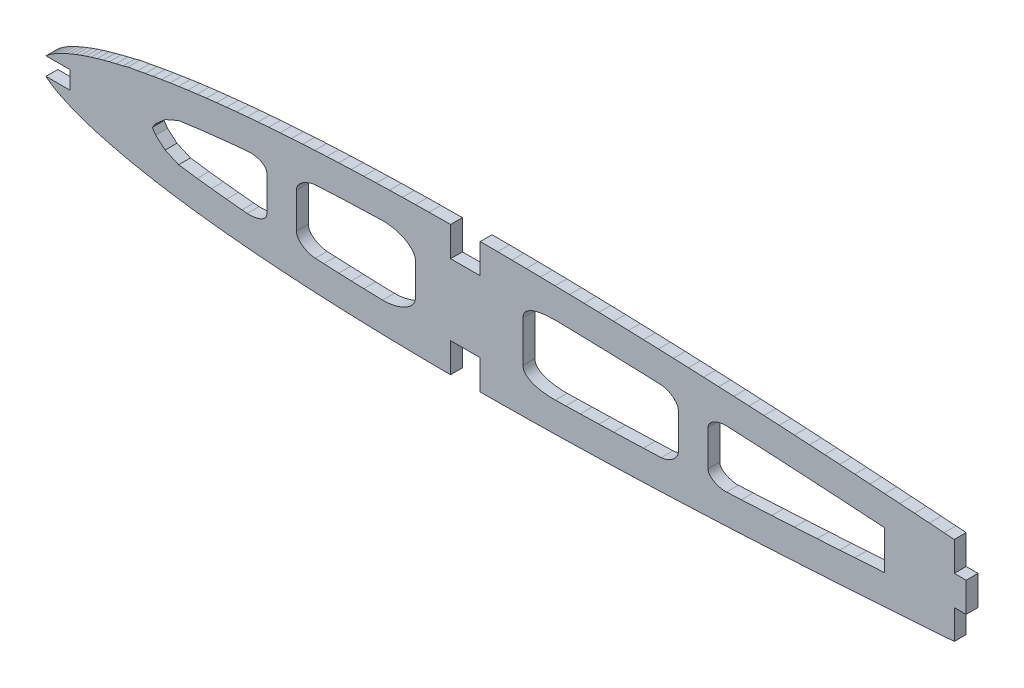
SolidWorks part; units mm, degrees
ref_plane "前视基准面" through (0, 0, 0) normal (0, 0, 1) x (1, 0, 0)
ref_plane "上视基准面" through (0, 0, 0) normal (0, 1, 0) x (1, 0, 0)
ref_plane "右视基准面" through (0, 0, 0) normal (1, 0, 0) x (0, 0, -1)
sketch "Model" plane through (0, 0, 0) normal (0, 0, 1) x (1, 0, 0)
  line L0 (365.1559, -97.3973) -> (369.2164, -97.3973)
  line L1 (369.2164, -97.3973) -> (369.2164, -100.3973)
  line L2 (369.2164, -100.3973) -> (365.1559, -100.3973)
  line L3 (438.4064, -87.9083) -> (438.4104, -92.9083)
  line L4 (438.4104, -92.9083) -> (433.4104, -92.9143)
  line L5 (433.4104, -92.9143) -> (433.4064, -87.9143)
  line L6 (438.4064, -109.8863) -> (438.4124, -104.8863)
  line L7 (438.4124, -104.8863) -> (433.4124, -104.8803)
  line L8 (433.4124, -104.8803) -> (433.4064, -109.8803)
  line L9 (518.3903, -91.444) -> (516.6664, -91.3183)
  line L10 (516.6664, -91.3183) -> (514.1714, -91.1393)
  line L11 (514.1714, -91.1393) -> (511.6764, -90.9633)
  line L12 (511.6764, -90.9633) -> (509.1804, -90.7903)
  line L13 (509.1804, -90.7903) -> (506.6554, -90.6183)
  line L14 (506.6554, -90.6183) -> (504.1314, -90.4503)
  line L15 (504.1314, -90.4503) -> (501.6054, -90.2873)
  line L16 (501.6054, -90.2873) -> (499.0594, -90.1283)
  line L17 (499.0594, -90.1283) -> (496.5144, -89.9743)
  line L18 (496.5144, -89.9743) -> (493.9684, -89.8233)
  line L19 (493.9684, -89.8233) -> (491.4134, -89.6743)
  line L20 (491.4134, -89.6743) -> (488.8584, -89.5283)
  line L21 (488.8584, -89.5283) -> (486.3034, -89.3863)
  line L22 (486.3034, -89.3863) -> (483.7484, -89.2513)
  line L23 (483.7484, -89.2513) -> (481.1944, -89.1213)
  line L24 (481.1944, -89.1213) -> (478.6384, -88.9983)
  line L25 (478.6384, -88.9983) -> (476.0924, -88.8813)
  line L26 (476.0924, -88.8813) -> (473.5474, -88.7693)
  line L27 (473.5474, -88.7693) -> (471.0014, -88.6633)
  line L28 (471.0014, -88.6633) -> (468.4764, -88.5643)
  line L29 (468.4764, -88.5643) -> (465.9524, -88.4703)
  line L30 (465.9524, -88.4703) -> (463.4264, -88.3833)
  line L31 (463.4264, -88.3833) -> (460.9314, -88.3033)
  line L32 (460.9314, -88.3033) -> (458.4364, -88.2303)
  line L33 (458.4364, -88.2303) -> (455.9404, -88.1633)
  line L34 (455.9404, -88.1633) -> (453.4854, -88.1043)
  line L35 (453.4854, -88.1043) -> (451.0314, -88.0523)
  line L36 (451.0314, -88.0523) -> (448.5764, -88.0073)
  line L37 (448.5764, -88.0073) -> (446.1704, -87.9703)
  line L38 (446.1704, -87.9703) -> (443.7664, -87.9423)
  line L39 (443.7664, -87.9423) -> (441.3604, -87.9213)
  line L40 (441.3604, -87.9213) -> (438.4064, -87.9083)
  line L42 (387.5324, -95.6683) -> (390.6644, -95.2413)
  line L43 (390.6644, -95.2413) -> (393.0784, -94.9513)
  line L44 (393.0784, -94.9513) -> (395.6144, -94.6733)
  line L45 (395.6144, -94.6733) -> (398.2099, -94.4193)
  line L46 (398.2099, -94.4193) -> (399.256, -94.3267)
  line L47 (410.7501, -93.5242) -> (412.0079, -93.4582)
  line L48 (412.0079, -93.4582) -> (414.9885, -93.3234)
  line L49 (414.9885, -93.3234) -> (416.6574, -93.2563)
  line L50 (416.6574, -93.2563) -> (418.7714, -93.1823)
  line L51 (418.7714, -93.1823) -> (421.9864, -93.0883)
  line L52 (421.9343, -104.7047) -> (418.7714, -104.6123)
  line L53 (418.7714, -104.6123) -> (416.6574, -104.5383)
  line L54 (416.6574, -104.5383) -> (414.5434, -104.4533)
  line L55 (414.5434, -104.4533) -> (412.0079, -104.3363)
  line L56 (412.0079, -104.3363) -> (410.5909, -104.2619)
  line L57 (399.1076, -103.4547) -> (398.2099, -103.3753)
  line L58 (398.2099, -103.3753) -> (395.6144, -103.1213)
  line L59 (395.6144, -103.1213) -> (393.0784, -102.8433)
  line L60 (393.0784, -102.8433) -> (390.6644, -102.5533)
  line L61 (390.6644, -102.5533) -> (387.5324, -102.1263)
  line L62 (451.3201, -93.0601) -> (452.8362, -93.0905)
  line L63 (452.8362, -93.0905) -> (455.2997, -93.1479)
  line L64 (455.2997, -93.1479) -> (458.4364, -93.2303)
  line L65 (458.4364, -93.2303) -> (460.9314, -93.3033)
  line L66 (460.9314, -93.3033) -> (465.9524, -93.4703)
  line L67 (465.9524, -93.4703) -> (468.8582, -93.5804)
  line L68 (479.9184, -94.063) -> (482.4714, -94.1863)
  line L69 (482.4714, -94.1863) -> (487.5809, -94.4573)
  line L70 (487.5809, -94.4573) -> (491.4134, -94.6743)
  line L71 (491.4134, -94.6743) -> (495.2414, -94.8988)
  line L72 (495.2414, -94.8988) -> (499.0594, -95.1283)
  line L73 (499.0594, -95.1283) -> (501.6054, -95.2873)
  line L74 (501.6054, -95.2873) -> (506.6554, -95.6183)
  line L75 (506.6554, -102.1763) -> (501.6054, -102.5073)
  line L76 (501.6054, -102.5073) -> (499.0594, -102.6663)
  line L77 (499.0594, -102.6663) -> (495.2414, -102.8958)
  line L78 (495.2414, -102.8958) -> (491.4134, -103.1203)
  line L79 (491.4134, -103.1203) -> (487.5809, -103.3373)
  line L80 (487.5809, -103.3373) -> (482.4714, -103.6083)
  line L81 (482.4714, -103.6083) -> (479.9656, -103.7292)
  line L82 (468.9559, -104.2104) -> (465.9524, -104.3243)
  line L83 (465.9524, -104.3243) -> (460.9314, -104.4913)
  line L84 (460.9314, -104.4913) -> (458.4364, -104.5643)
  line L85 (458.4364, -104.5643) -> (455.2997, -104.6467)
  line L86 (455.2997, -104.6467) -> (452.8362, -104.704)
  line L87 (452.8362, -104.704) -> (451.0861, -104.7391)
  line L88 (387.5324, -95.6683) -> (385.2532, -96.6702)
  line L89 (385.2532, -96.6702) -> (383.6712, -98.0522)
  line L90 (383.6712, -98.0522) -> (383.078, -98.8973)
  line L91 (387.5324, -102.1263) -> (385.2532, -101.1243)
  line L92 (385.2532, -101.1243) -> (383.6712, -99.7423)
  line L93 (383.6712, -99.7423) -> (383.078, -98.8973)
  line L94 (427.4864, -96.2466) -> (427.4864, -101.548)
  line L95 (445.635, -95.4141) -> (445.635, -102.3805)
  line L96 (407.4071, -95.8973) -> (407.4071, -101.8973)
  line L97 (402.4071, -101.8973) -> (402.4071, -95.8973)
  line L98 (476.8379, -95.8973) -> (476.8379, -101.8973)
  line L99 (471.8379, -101.8973) -> (471.8379, -95.8973)
  line L100 (520.3903, -98.8973) -> (520.3903, -96.3973)
  line L101 (520.3903, -98.8973) -> (520.3903, -101.3973)
  line L102 (520.3903, -96.3973) -> (518.3903, -96.3973)
  line L103 (520.3903, -101.3973) -> (518.3903, -101.3973)
  line L104 (518.3903, -96.3973) -> (518.3903, -91.444)
  line L105 (518.3903, -101.3973) -> (518.3903, -106.3499)
  line L106 (506.6554, -95.6183) -> (506.6554, -102.1763)
  line L107 (433.4064, -87.9143) -> (429.7654, -87.9423)
  line L108 (429.7654, -87.9423) -> (427.4864, -87.9723)
  line L109 (427.4864, -87.9723) -> (425.2864, -88.0113)
  line L110 (425.2864, -88.0113) -> (423.0864, -88.0593)
  line L111 (423.0864, -88.0593) -> (420.8864, -88.1173)
  line L112 (420.8864, -88.1173) -> (418.7714, -88.1823)
  line L113 (418.7714, -88.1823) -> (416.6574, -88.2563)
  line L114 (416.6574, -88.2563) -> (414.5434, -88.3413)
  line L115 (414.5434, -88.3413) -> (412.5224, -88.4323)
  line L116 (412.5224, -88.4323) -> (410.5024, -88.5343)
  line L117 (410.5024, -88.5343) -> (408.4824, -88.6463)
  line L118 (408.4824, -88.6463) -> (406.5644, -88.7643)
  line L119 (406.5644, -88.7643) -> (404.6474, -88.8943)
  line L120 (404.6474, -88.8943) -> (402.7304, -89.0353)
  line L121 (402.7304, -89.0353) -> (400.9214, -89.1793)
  line L122 (400.9214, -89.1793) -> (399.1134, -89.3353)
  line L123 (399.1134, -89.3353) -> (397.3064, -89.5033)
  line L124 (397.3064, -89.5033) -> (395.6144, -89.6733)
  line L125 (395.6144, -89.6733) -> (393.9234, -89.8543)
  line L126 (393.9234, -89.8543) -> (392.2334, -90.0483)
  line L127 (392.2334, -90.0483) -> (390.6644, -90.2413)
  line L128 (390.6644, -90.2413) -> (389.0974, -90.4483)
  line L129 (389.0974, -90.4483) -> (387.5324, -90.6683)
  line L130 (387.5324, -90.6683) -> (386.0934, -90.8853)
  line L131 (386.0934, -90.8853) -> (384.6574, -91.1153)
  line L132 (384.6574, -91.1153) -> (383.2234, -91.3593)
  line L133 (383.2234, -91.3593) -> (381.9184, -91.5963)
  line L134 (381.9184, -91.5963) -> (380.6174, -91.8473)
  line L135 (380.6174, -91.8473) -> (379.0174, -92.1113)
  line L136 (379.0174, -92.1113) -> (378.1544, -92.3693)
  line L137 (378.1544, -92.3693) -> (376.9934, -92.6403)
  line L138 (376.9934, -92.6403) -> (375.8364, -92.9273)
  line L139 (375.8364, -92.9273) -> (374.8164, -93.1963)
  line L140 (374.8164, -93.1963) -> (373.8004, -93.4803)
  line L141 (373.8004, -93.4803) -> (372.7894, -93.7843)
  line L142 (372.7894, -93.7843) -> (371.9164, -94.0643)
  line L143 (371.9164, -94.0643) -> (371.0504, -94.3633)
  line L144 (371.0504, -94.3633) -> (370.1914, -94.6823)
  line L145 (370.1914, -94.6823) -> (369.4714, -94.9713)
  line L146 (369.4714, -94.9713) -> (368.7584, -95.2773)
  line L147 (368.7584, -95.2773) -> (368.0524, -95.6003)
  line L148 (368.0524, -95.6003) -> (367.4844, -95.8783)
  line L149 (367.4844, -95.8783) -> (366.9254, -96.1743)
  line L150 (366.9254, -96.1743) -> (366.3794, -96.4943)
  line L151 (366.3794, -96.4943) -> (365.9634, -96.7673)
  line L152 (365.9634, -96.7673) -> (365.5614, -97.0603)
  line L153 (365.5614, -97.0603) -> (365.1784, -97.3763)
  line L154 (365.1784, -97.3763) -> (365.1559, -97.3973)
  line L155 (438.4064, -109.8863) -> (441.3604, -109.8723)
  line L156 (441.3604, -109.8723) -> (443.7664, -109.8523)
  line L157 (443.7664, -109.8523) -> (446.1704, -109.8233)
  line L158 (446.1704, -109.8233) -> (448.5764, -109.7873)
  line L159 (448.5764, -109.7873) -> (451.0314, -109.7423)
  line L160 (451.0314, -109.7423) -> (453.4854, -109.6903)
  line L161 (453.4854, -109.6903) -> (455.9404, -109.6313)
  line L162 (455.9404, -109.6313) -> (458.4364, -109.5643)
  line L163 (458.4364, -109.5643) -> (460.9314, -109.4913)
  line L164 (460.9314, -109.4913) -> (463.4264, -109.4113)
  line L165 (463.4264, -109.4113) -> (465.9524, -109.3233)
  line L166 (465.9524, -109.3233) -> (468.4764, -109.2303)
  line L167 (468.4764, -109.2303) -> (471.0014, -109.1303)
  line L168 (471.0014, -109.1303) -> (473.5474, -109.0243)
  line L169 (473.5474, -109.0243) -> (476.0924, -108.9133)
  line L170 (476.0924, -108.9133) -> (478.6384, -108.7963)
  line L171 (478.6384, -108.7963) -> (481.1944, -108.6723)
  line L172 (481.1944, -108.6723) -> (483.7484, -108.5433)
  line L173 (483.7484, -108.5433) -> (486.3034, -108.4073)
  line L174 (486.3034, -108.4073) -> (488.8584, -108.2663)
  line L175 (488.8584, -108.2663) -> (491.4134, -108.1203)
  line L176 (491.4134, -108.1203) -> (493.9684, -107.9703)
  line L177 (493.9684, -107.9703) -> (496.5144, -107.8193)
  line L178 (496.5144, -107.8193) -> (499.0594, -107.6653)
  line L179 (499.0594, -107.6653) -> (501.6054, -107.5063)
  line L180 (501.6054, -107.5063) -> (504.1314, -107.3433)
  line L181 (504.1314, -107.3433) -> (506.6554, -107.1753)
  line L182 (506.6554, -107.1753) -> (509.1804, -107.0033)
  line L183 (509.1804, -107.0033) -> (511.6764, -106.8313)
  line L184 (511.6764, -106.8313) -> (514.1714, -106.6553)
  line L185 (514.1714, -106.6553) -> (516.6664, -106.4763)
  line L186 (516.6664, -106.4763) -> (518.3903, -106.3499)
  line L187 (365.1559, -100.3973) -> (365.1784, -100.4183)
  line L188 (365.1784, -100.4183) -> (365.5614, -100.7343)
  line L189 (365.5614, -100.7343) -> (365.9634, -101.0273)
  line L190 (365.9634, -101.0273) -> (366.3794, -101.2993)
  line L191 (366.3794, -101.2993) -> (366.9254, -101.6203)
  line L192 (366.9254, -101.6203) -> (367.4844, -101.9153)
  line L193 (367.4844, -101.9153) -> (368.0524, -102.1933)
  line L194 (368.0524, -102.1933) -> (368.7584, -102.5173)
  line L195 (368.7584, -102.5173) -> (369.4714, -102.8233)
  line L196 (369.4714, -102.8233) -> (370.1914, -103.1113)
  line L197 (370.1914, -103.1113) -> (371.0504, -103.4313)
  line L198 (371.0504, -103.4313) -> (371.9164, -103.7293)
  line L199 (371.9164, -103.7293) -> (372.7894, -104.0103)
  line L200 (372.7894, -104.0103) -> (373.8004, -104.3133)
  line L201 (373.8004, -104.3133) -> (374.8164, -104.5983)
  line L202 (374.8164, -104.5983) -> (375.8364, -104.8673)
  line L203 (375.8364, -104.8673) -> (376.9934, -105.1543)
  line L204 (376.9934, -105.1543) -> (378.1544, -105.4253)
  line L205 (378.1544, -105.4253) -> (379.3184, -105.6803)
  line L206 (379.3184, -105.6803) -> (380.6174, -105.9473)
  line L207 (380.6174, -105.9473) -> (381.9184, -106.1983)
  line L208 (381.9184, -106.1983) -> (383.2234, -106.4343)
  line L209 (383.2234, -106.4343) -> (384.6574, -106.6793)
  line L210 (384.6574, -106.6793) -> (386.0934, -106.9093)
  line L211 (386.0934, -106.9093) -> (387.5324, -107.1253)
  line L212 (387.5324, -107.1253) -> (389.0974, -107.3463)
  line L213 (389.0974, -107.3463) -> (390.6644, -107.5523)
  line L214 (390.6644, -107.5523) -> (392.2334, -107.7463)
  line L215 (392.2334, -107.7463) -> (393.9234, -107.9403)
  line L216 (393.9234, -107.9403) -> (395.6144, -108.1213)
  line L217 (395.6144, -108.1213) -> (397.3064, -108.2903)
  line L218 (397.3064, -108.2903) -> (399.1134, -108.4583)
  line L219 (399.1134, -108.4583) -> (400.9214, -108.6143)
  line L220 (400.9214, -108.6143) -> (402.7304, -108.7593)
  line L221 (402.7304, -108.7593) -> (404.6474, -108.9003)
  line L222 (404.6474, -108.9003) -> (406.5644, -109.0293)
  line L223 (406.5644, -109.0293) -> (408.4824, -109.1473)
  line L224 (408.4824, -109.1473) -> (410.5024, -109.2603)
  line L225 (410.5024, -109.2603) -> (412.5224, -109.3613)
  line L226 (412.5224, -109.3613) -> (414.5434, -109.4523)
  line L227 (414.5434, -109.4523) -> (416.6574, -109.5373)
  line L228 (416.6574, -109.5373) -> (418.7714, -109.6123)
  line L229 (418.7714, -109.6123) -> (420.8864, -109.6773)
  line L230 (420.8864, -109.6773) -> (423.0864, -109.7353)
  line L231 (423.0864, -109.7353) -> (425.2864, -109.7833)
  line L232 (425.2864, -109.7833) -> (427.4864, -109.8213)
  line L233 (427.4864, -109.8213) -> (429.7654, -109.8513)
  line L234 (429.7654, -109.8513) -> (433.4064, -109.8803)
  spline S0 degree 3 poles (421.9864, -93.0883) (424.0996, -93.0265) (427.4864, -94.1325) (427.4864, -96.2466) knots 0 0 0 0 6.342328 6.342328 6.342328 6.342328
  spline S1 degree 3 poles (421.9343, -104.7047) (424.0623, -104.767) (427.4864, -103.6769) (427.4864, -101.548) knots 0 0 0 0 6.386793 6.386793 6.386793 6.386793
  spline S2 degree 3 poles (445.635, -95.4141) (445.635, -93.363) (449.2694, -93.019) (451.3201, -93.0601) knots 0 0 0 0 6.153175 6.153175 6.153175 6.153175
  spline S3 degree 3 poles (445.635, -102.3805) (445.635, -104.3603) (449.1067, -104.7787) (451.0861, -104.7391) knots 0 0 0 0 5.93954 5.93954 5.93954 5.93954
  spline S4 degree 3 poles (399.256, -94.3267) (400.425, -94.2232) (402.4071, -94.7237) (402.4071, -95.8973) knots 0 0 0 0 3.52078 3.52078 3.52078 3.52078
  spline S5 degree 3 poles (399.1076, -103.4547) (400.319, -103.5619) (402.4071, -103.1135) (402.4071, -101.8973) knots 0 0 0 0 3.648605 3.648605 3.648605 3.648605
  spline S6 degree 3 poles (410.7501, -93.5242) (409.3855, -93.5959) (407.4071, -94.5307) (407.4071, -95.8973) knots 0 0 0 0 4.09968 4.09968 4.09968 4.09968
  spline S7 degree 3 poles (410.5909, -104.2619) (409.2708, -104.1926) (407.4071, -103.2192) (407.4071, -101.8973) knots 0 0 0 0 3.965934 3.965934 3.965934 3.965934
  spline S8 degree 3 poles (468.8582, -93.5804) (470.1154, -93.628) (471.8379, -94.6391) (471.8379, -95.8973) knots 0 0 0 0 3.774504 3.774504 3.774504 3.774504
  spline S9 degree 3 poles (468.9559, -104.2104) (470.1869, -104.1638) (471.8379, -103.1291) (471.8379, -101.8973) knots 0 0 0 0 3.695535 3.695535 3.695535 3.695535
  spline S10 degree 3 poles (479.9184, -94.063) (478.7247, -94.0054) (476.8379, -94.7022) (476.8379, -95.8973) knots 0 0 0 0 3.585193 3.585193 3.585193 3.585193
  spline S11 degree 3 poles (479.9656, -103.7292) (478.7588, -103.7875) (476.8379, -103.1055) (476.8379, -101.8973) knots 0 0 0 0 3.624712 3.624712 3.624712 3.624712
  point P36 (0, 0)
  point P249 (518.5712, -91.4752)
  point P250 (518.4066, -91.444)
  point P251 (379.0361, -92.108)
extrude "凸台-拉伸1" add sketch "Model" along normal blind 2
